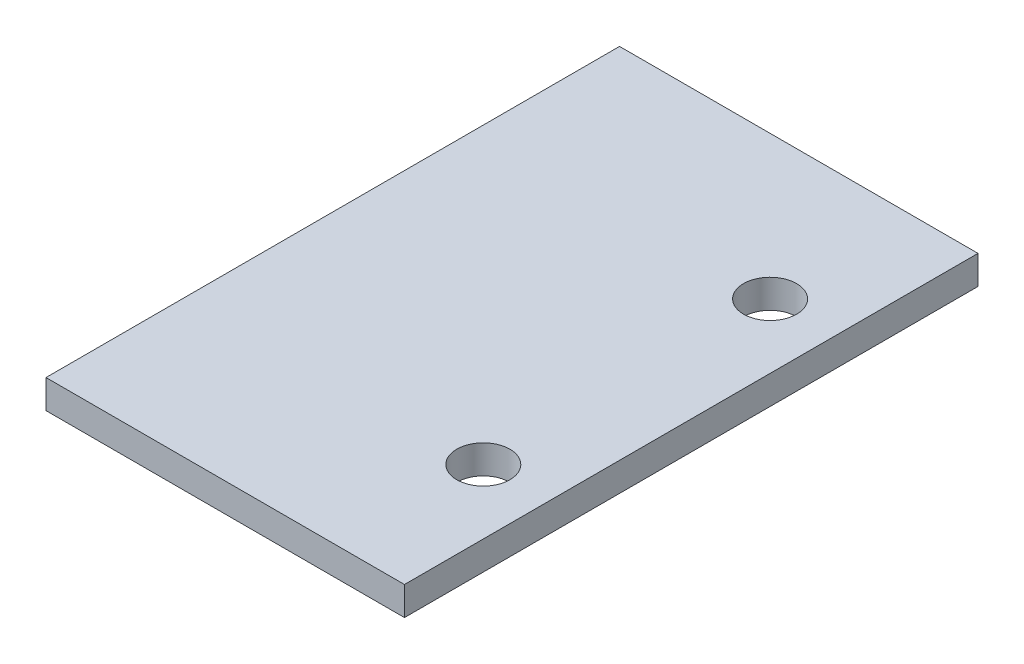
SolidWorks part; units mm, degrees
ref_plane "Front Plane" through (0, 0, 0) normal (0, 0, 1) x (1, 0, 0)
ref_plane "Top Plane" through (0, 0, 0) normal (0, 1, 0) x (1, 0, 0)
ref_plane "Right Plane" through (0, 0, 0) normal (1, 0, 0) x (0, 0, -1)
sketch "Sketch1" plane through (0, 0, 0) normal (0, 1, 0) x (1, 0, 0)
  line L0 (20.5, 40) -> (20.5, 30) construction
  line L1 (0, 0) -> (25, 0)
  line L2 (0, 0) -> (0, 40)
  line L3 (0, 40) -> (25, 40)
  line L4 (25, 0) -> (25, 40)
  line L5 (20.5, 30) -> (20.5, 10) construction
  line L6 (20.5, 10) -> (20.5, 0) construction
  circle A0 centre (20.5, 30) radius 1.85
  circle A1 centre (20.5, 10) radius 1.85
  dimension "D3" = 4.5
  dimension "D4" = 3.7
  dimension "D1" = 25
  dimension "D2" = 40
  dimension "D5" = 10
extrude "Boss-Extrude1" add sketch "Sketch1" along normal blind 2
